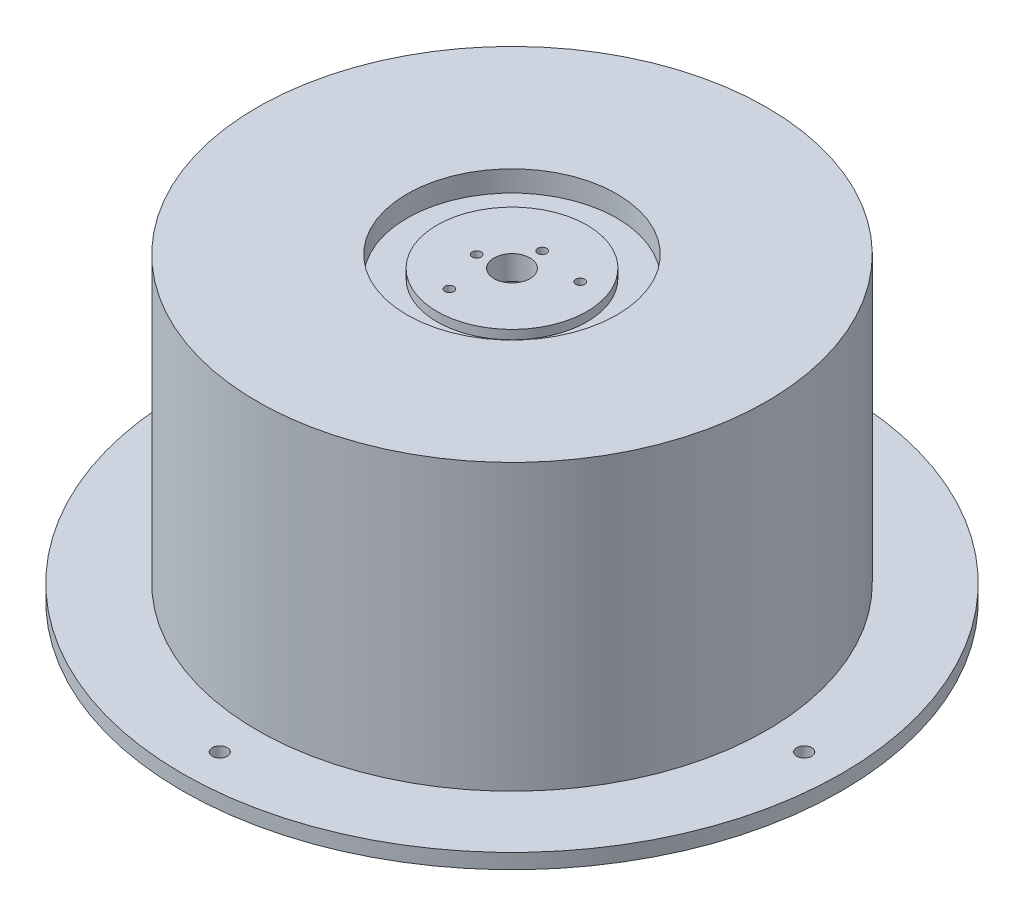
SolidWorks part; units mm, degrees
material "6061 Alloy"
ref_plane "Front Plane" through (0, 0, 0) normal (0, 0, 1) x (1, 0, 0)
ref_plane "Top Plane" through (0, 0, 0) normal (0, 1, 0) x (1, 0, 0)
ref_plane "Right Plane" through (0, 0, 0) normal (1, 0, 0) x (0, 0, -1)
sketch "Sketch1" plane through (0, 0, 0) normal (0, 0, 1) x (1, 0, 0)
  line L0 (0, 0) -> (0, 162.25) construction
  line L1 (80, 0) -> (80, 88)
  line L4 (35, 100) -> (85, 100)
  line L5 (85, 100) -> (85, 0)
  line L6 (85, 0) -> (80, 0)
  line L7 (35, 100) -> (35, 93)
  line L8 (35, 93) -> (25, 93)
  line L10 (6, 88) -> (80, 88)
  line L11 (25, 93) -> (25, 96)
  line L12 (25, 96) -> (6, 96)
  line L17 (6, 96) -> (6, 88)
  dimension "D1" = 7
  dimension "D2" = 170
  dimension "D3" = 5
  dimension "D4" = 5
  dimension "D5" = 100
  dimension "D6" = 8
  dimension "D7" = 70
  dimension "D9" = 50
  dimension "D12" = 12
revolve "Revolve1" add sketch "Sketch1" angle 360 about L0
sketch "Sketch2" plane through (0, 96, 0) normal (0, 1, 0) x (1, 0, 0)
  circle A0 centre (0, 10.0525) radius 1.5
  circle A1 centre (-9.8881, -1.8838) radius 1.5
  circle A2 centre (-4.4753, -16.408) radius 1.5
  circle A3 centre (15.2685, 7.4914) radius 1.5
  dimension "D1" = 3
  dimension "D2" = 3
  dimension "D4" = 15.5
  dimension "D7" = 3
  dimension "D9" = 3
  dimension "D10" = 17.0074
  dimension "D11" = 15.4818
  dimension "D3" = 10.0525
  dimension "D5" = 10.0659
  dimension "D6" = 15.5
  dimension "D8" = 17.0074
extrude "Cut-Extrude1" cut sketch "Sketch2" against normal up to next contours A3 | A0 | A1 | A2
sketch "Sketch3" plane through (0, 0, 0) normal (0, -1, 0) x (1, 0, 0)
  circle A0 centre (0, 0) radius 85
  circle A1 centre (0, 0) radius 110
  circle A2 centre (0, 97.5) radius 2.5
  circle A3 centre (97.5, 0) radius 2.5
  circle A4 centre (0, -97.5) radius 2.5
  circle A5 centre (-97.5, 0) radius 2.5
  dimension "D1" = 170
  dimension "D2" = 220
  dimension "D3" = 5
  dimension "D4" = 97.5
  dimension "D5" = 4
extrude "Boss-Extrude1" add sketch "Sketch3" against normal blind 5
